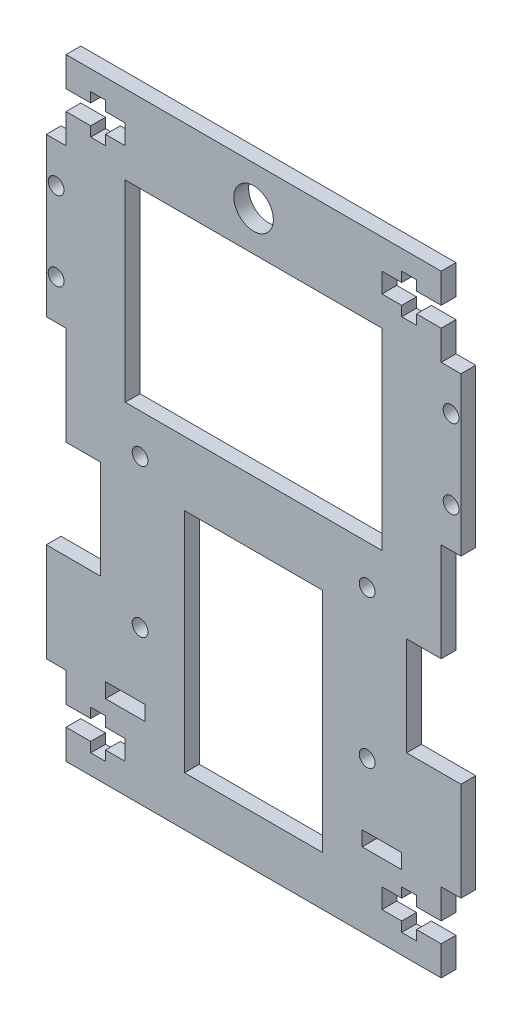
SolidWorks part; units mm, degrees
ref_plane "前视" through (0, 0, 0) normal (0, 0, 1) x (1, 0, 0)
ref_plane "上视" through (0, 0, 0) normal (0, 1, 0) x (1, 0, 0)
ref_plane "右视" through (0, 0, 0) normal (1, 0, 0) x (0, 0, -1)
sketch "草图1" plane through (0, 0, 0) normal (0, 0, 1) x (1, 0, 0)
  line L0 (0, 210.7736) -> (0, 0) construction
  line L1 (-42, 54) -> (-42, 38)
  line L2 (-38, 18) -> (-31, 18)
  line L3 (-31, 18) -> (-31, -2)
  line L4 (38, 86) -> (-38, 86)
  line L5 (-38, 86) -> (-38, 80)
  line L6 (-31, -2) -> (-38, -2)
  line L7 (-57.1558, 78) -> (-15.5606, 78) construction
  line L8 (-38, -38) -> (38, -38)
  line L9 (-14, -28) -> (-14, 18)
  line L10 (-30, -20) -> (-22, -20)
  line L11 (-30, -20) -> (-30, -23)
  line L12 (-30, -23) -> (-22, -23)
  line L13 (-22, -20) -> (-22, -23)
  line L14 (42, -30) -> (14.2627, -30) construction
  line L15 (14, -28) -> (-14, -28)
  line L16 (-38, 80) -> (-33, 80)
  line L17 (-33, 80) -> (-33, 82)
  line L18 (-33, 82) -> (-30, 82)
  line L19 (-30, 82) -> (-30, 80)
  line L20 (-30, 80) -> (-26, 80)
  line L21 (-26, 80) -> (-26, 76)
  line L22 (-38, 70) -> (-42, 70)
  line L23 (-42, 70) -> (-42, 54)
  line L24 (-38, -2) -> (-42, -2)
  line L25 (-14, 18) -> (14, 18)
  line L26 (57.1558, 78) -> (15.5606, 78) construction
  line L27 (-42, -2) -> (-42, -22)
  line L28 (-42, -22) -> (-38, -22)
  line L29 (-42, -30) -> (-14.2627, -30) construction
  line L30 (-38, -32) -> (-33, -32)
  line L31 (-30, 76) -> (-26, 76)
  line L32 (-30, 74) -> (-30, 76)
  line L33 (-33, 74) -> (-30, 74)
  line L34 (-33, 76) -> (-33, 74)
  line L35 (-38, 76) -> (-33, 76)
  line L36 (-33, -32) -> (-33, -34)
  line L37 (-33, -34) -> (-30, -34)
  line L38 (-30, -34) -> (-30, -32)
  line L39 (-30, -32) -> (-26, -32)
  line L40 (-26, -32) -> (-26, -28)
  line L41 (-30, -28) -> (-26, -28)
  line L42 (-30, -26) -> (-30, -28)
  line L43 (-33, -26) -> (-30, -26)
  line L44 (-33, -28) -> (-33, -26)
  line L45 (-38, -28) -> (-33, -28)
  line L46 (42, 38) -> (38, 38)
  line L47 (38, 76) -> (38, 70)
  line L48 (38, 38) -> (38, 18)
  line L49 (-38, -32) -> (-38, -38)
  line L50 (-38, -22) -> (-38, -28)
  line L51 (-42, -22) -> (-42.1839, -21.2575)
  line L52 (38, -2) -> (42, -2)
  line L53 (-38, 38) -> (-38, 18)
  line L54 (-38, 76) -> (-38, 70)
  line L55 (38, -22) -> (38, -28)
  line L56 (38, -32) -> (38, -38)
  line L57 (38, -28) -> (33, -28)
  line L58 (33, -28) -> (33, -26)
  line L59 (33, -26) -> (30, -26)
  line L60 (30, -26) -> (30, -28)
  line L61 (30, -28) -> (26, -28)
  line L62 (26, -32) -> (26, -28)
  line L63 (30, -32) -> (26, -32)
  line L64 (30, -34) -> (30, -32)
  line L65 (33, -34) -> (30, -34)
  line L66 (33, -32) -> (33, -34)
  line L67 (38, 76) -> (33, 76)
  line L68 (33, 76) -> (33, 74)
  line L69 (33, 74) -> (30, 74)
  line L70 (30, 74) -> (30, 76)
  line L71 (30, 76) -> (26, 76)
  line L72 (38, -32) -> (33, -32)
  line L73 (42, -22) -> (38, -22)
  line L74 (42, -2) -> (42, -22)
  line L75 (14, 18) -> (14, -28)
  line L77 (42, 70) -> (42, 54)
  line L78 (38, 70) -> (42, 70)
  line L79 (26, 80) -> (26, 76)
  line L80 (30, 80) -> (26, 80)
  line L81 (30, 82) -> (30, 80)
  line L82 (33, 82) -> (30, 82)
  line L83 (33, 80) -> (33, 82)
  line L84 (38, 80) -> (33, 80)
  line L85 (22, -20) -> (22, -23)
  line L86 (30, -23) -> (22, -23)
  line L87 (30, -20) -> (30, -23)
  line L88 (30, -20) -> (22, -20)
  line L89 (31, -2) -> (38, -2)
  line L90 (38, 86) -> (38, 80)
  line L91 (31, 18) -> (31, -2)
  line L92 (38, 18) -> (31, 18)
  line L93 (42, 54) -> (42, 38)
  line L94 (-62.2814, 8) -> (64.6194, 8) construction
  line L96 (-26, 31) -> (26, 31)
  line L97 (-26, 31) -> (-26, 70)
  line L98 (-26, 70) -> (26, 70)
  line L99 (26, 31) -> (26, 70)
  line L113 (-42, 38) -> (-38, 38)
  circle A0 centre (0, 78) radius 4
  circle A2 centre (-40, 62) radius 1.6
  circle A3 centre (40, 46) radius 1.6
  circle A4 centre (40, 62) radius 1.6
  circle A5 centre (-40, 46) radius 1.6
  circle A7 centre (-23, -7) radius 1.6
  circle A8 centre (-23, 23) radius 1.6
  circle A9 centre (23, -7) radius 1.6
  circle A10 centre (23, 23) radius 1.6
  point P20 (0, -38)
  point P42 (-26, 78)
  point P58 (-26, -30)
  point P110 (0, -28)
  point P114 (0, -7)
  point P116 (0, 86)
  point P117 (26, -30)
  point P118 (26, 78)
  point P133 (0, 86)
  point P135 (0, 0)
  dimension "D17" = 16
  dimension "D18" = 20
  dimension "D19" = 8
  dimension "D44" = 2
  dimension "D45" = 2
  dimension "D10" = 8
  dimension "D16" = 8
  dimension "D37" = 8
  dimension "D40" = 10
  dimension "D41" = 8
  dimension "D42" = 3.2
  dimension "D43" = 3.2
  dimension "D46" = 15
  dimension "D48" = 3.2
  dimension "D49" = 3.2
  dimension "D50" = 8
  dimension "D2" = 38
  dimension "D3" = 2
  dimension "D4" = 2
  dimension "D5" = 2
  dimension "D6" = 3
  dimension "D7" = 5
  dimension "D8" = 12
  dimension "D9" = 8
  dimension "D11" = 4
  dimension "D12" = 16
  dimension "D13" = 8
  dimension "D14" = 7
  dimension "D15" = 20
  dimension "D20" = 106
  dimension "D21" = 20
  dimension "D23" = 8
  dimension "D24" = 8
  dimension "D26" = 8
  dimension "D28" = 2
  dimension "D29" = 2
  dimension "D30" = 2
  dimension "D32" = 3
  dimension "D33" = 5
  dimension "D34" = 12
  dimension "D36" = 28
  dimension "D39" = 10
  dimension "D47" = 15
  dimension "D51" = 8
  dimension "D52" = 52
  dimension "D53" = 8
  dimension "D54" = 8
extrude "凸台-拉伸1" add sketch "草图1" along normal blind 3
